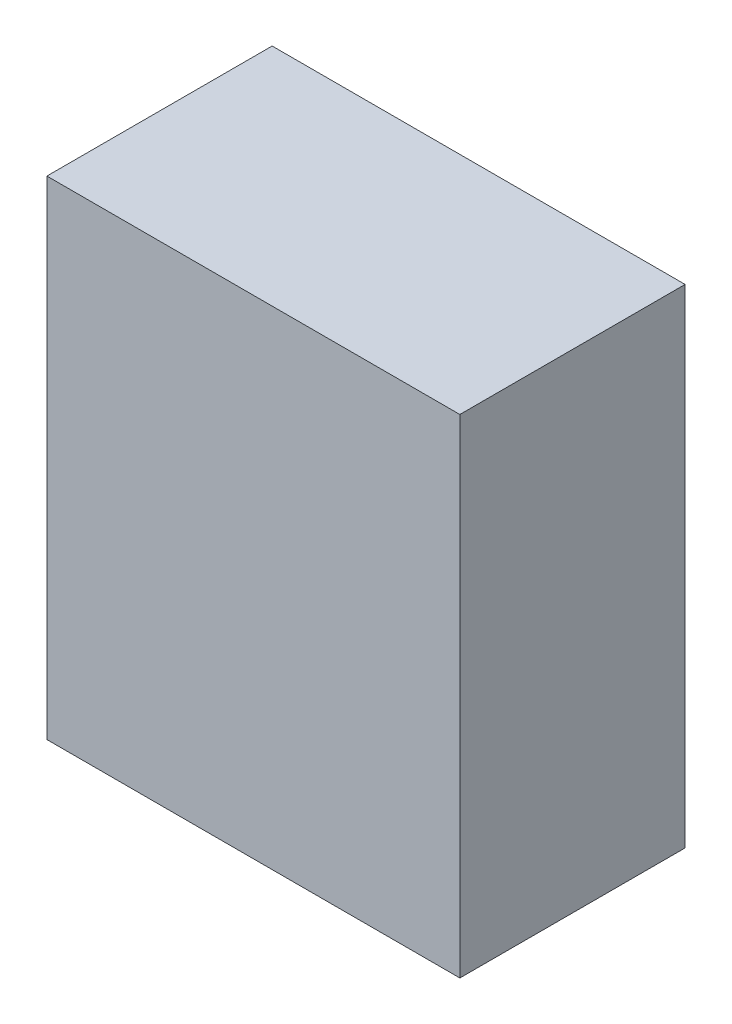
SolidWorks part; units mm, degrees
ref_plane "Front Plane" through (0, 0, 0) normal (1, 0, 0) x (0, 1, 0)
ref_plane "Top Plane" through (0, 0, 0) normal (0, 0, 1) x (0, 1, 0)
ref_plane "Right Plane" through (0, 0, 0) normal (0, 1, 0) x (-1, 0, 0)
sketch "Sketch1" plane through (0, 0, 0) normal (0, 0, 1) x (0, 1, 0)
  line L1 (0, 0) -> (82.55, 0)
  line L2 (0, 0) -> (0, 69.85)
  line L3 (0, 69.85) -> (82.55, 69.85)
  line L4 (82.55, 0) -> (82.55, 69.85)
extrude "Boss-Extrude1" add sketch "Sketch1" along normal blind 38.1
sketch "Sketch2" plane through (0, 0, 0) normal (0, 0, 1) x (0, 1, 0)
  line L0 (0, 69.85) -> (0, 0) construction
  circle A0 centre (0, 41.275) radius 12.7254
extrude "Cut-Extrude1" cut sketch "Sketch2" along normal blind 2.8194
